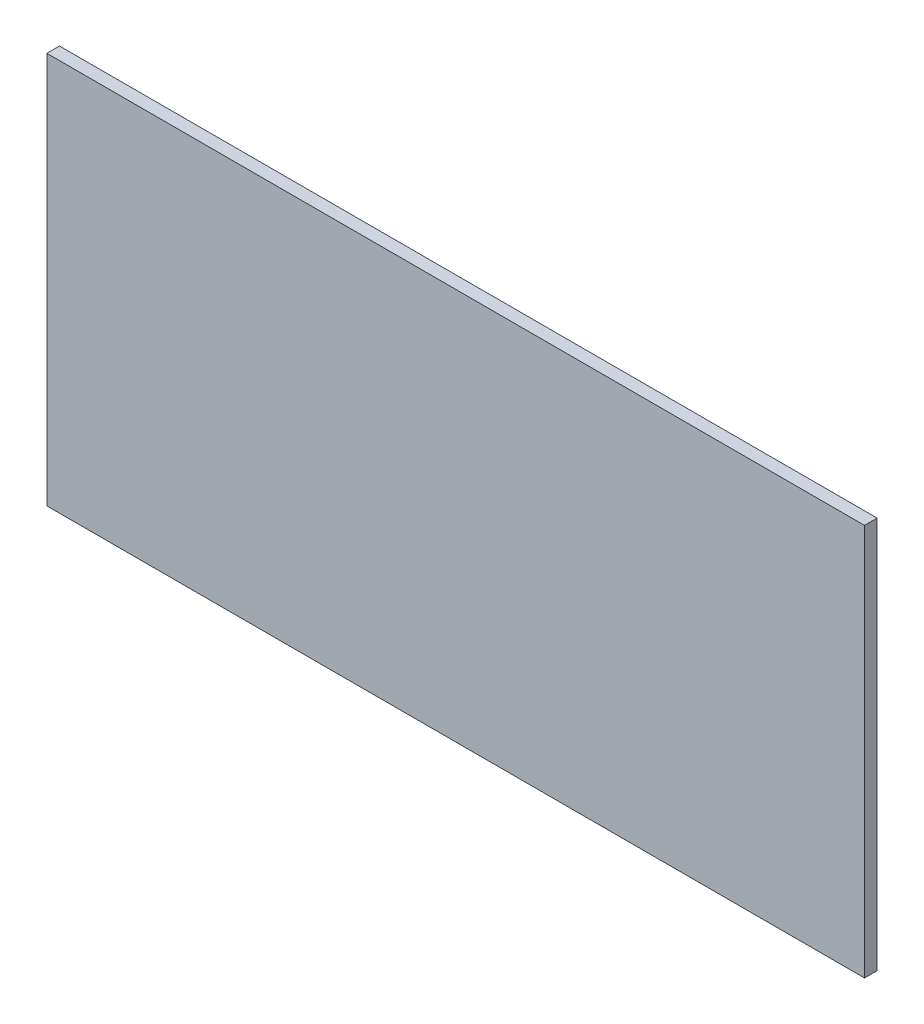
SolidWorks part; units mm, degrees
ref_plane "Front Plane" through (0, 0, 0) normal (0, 0, 1) x (1, 0, 0)
ref_plane "Top Plane" through (0, 0, 0) normal (0, 1, 0) x (1, 0, 0)
ref_plane "Right Plane" through (0, 0, 0) normal (1, 0, 0) x (0, 0, -1)
sketch "Sketch1" plane through (0, 0, 0) normal (0, 0, 1) x (1, 0, 0)
  line L1 (0, 0) -> (194, 0)
  line L2 (0, 0) -> (0, 93)
  line L3 (0, 93) -> (194, 93)
  line L4 (194, 0) -> (194, 93)
  dimension "D1" = 194
  dimension "D2" = 93
extrude "Profile" add sketch "Sketch1" along normal blind 3
equation "\"Profile_Depth\" = 3mm"
equation "\"D1@Profile\" = \"Profile_Depth\""
equation "\"EnvelopeWidth\" = 194mm"
equation "\"EnvelopeHeight\" = 93mm"
